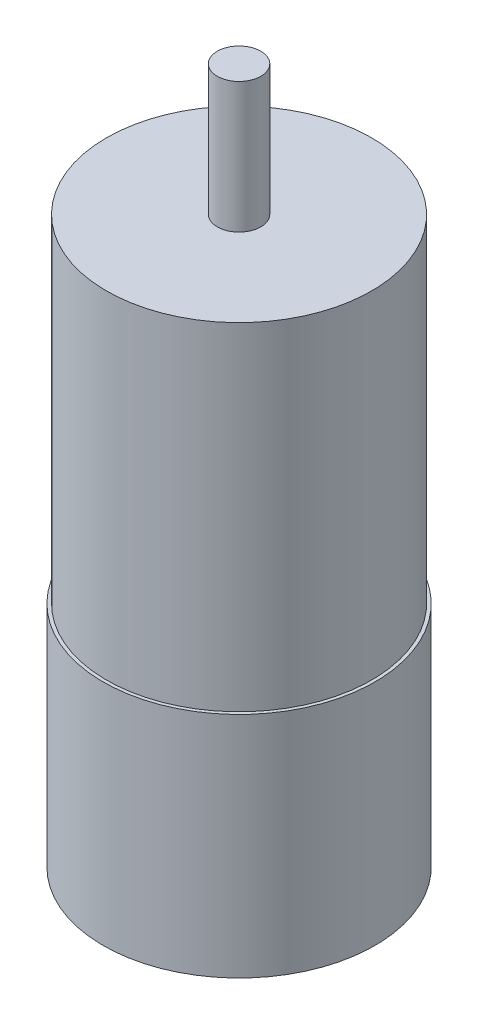
SolidWorks part; units mm, degrees
ref_plane "Front Plane" through (0, 0, 0) normal (0, 0, 1) x (1, 0, 0)
ref_plane "Top Plane" through (0, 0, 0) normal (0, 1, 0) x (1, 0, 0)
ref_plane "Right Plane" through (0, 0, 0) normal (1, 0, 0) x (0, 0, -1)
sketch "Esquisse2" plane through (0, 0, 0) normal (0, 0, 1) x (1, 0, 0)
  line L0 (0, 32.5333) -> (0, -19.4667) construction
  line L1 (0, 32.5333) -> (12.2, 32.5333)
  line L2 (0, 1.5333) -> (12.2, 1.5333)
  line L3 (12.2, 1.5333) -> (12.2, 32.5333)
  line L4 (0, -19.4667) -> (12.5, -19.4667)
  line L5 (12.5, -19.4667) -> (12.5, 1.5333)
  line L6 (12.5, 1.5333) -> (12.2, 1.5333)
  line L7 (0, 32.5333) -> (0, 44.5333)
  line L8 (0, 44.5333) -> (2, 44.5333)
  line L9 (2, 44.5333) -> (2, 32.5333)
  dimension "D1" = 12.2
  dimension "D2" = 52
  dimension "D3" = 31
  dimension "D4" = 21
  dimension "D5" = 12.5
  dimension "D6" = 12
  dimension "D7" = 2
revolve "Révolution2" add sketch "Esquisse2" angle 360 about L0
